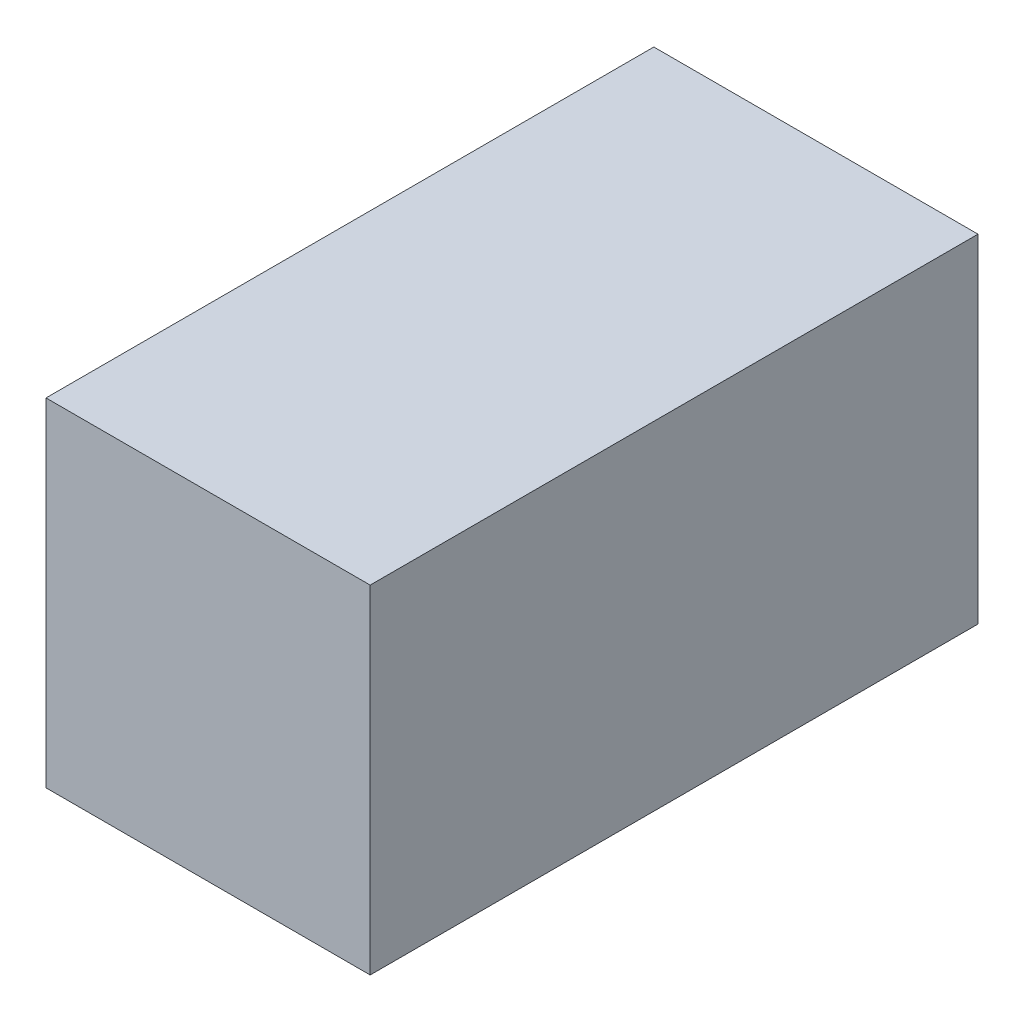
SolidWorks part; units mm, degrees
ref_plane "Front Plane" through (0, 0, 0) normal (0, 0, 1) x (1, 0, 0)
ref_plane "Top Plane" through (0, 0, 0) normal (0, 1, 0) x (1, 0, 0)
ref_plane "Right Plane" through (0, 0, 0) normal (1, 0, 0) x (0, 0, -1)
sketch "Sketch1" plane through (0, 0, 0) normal (1, 0, 0) x (0, 0, -1)
  line L1 (-25.0839, 20.618) -> (32.0661, 20.618)
  line L2 (-25.0839, 20.618) -> (-25.0839, -11.132)
  line L3 (-25.0839, -11.132) -> (32.0661, -11.132)
  line L4 (32.0661, 20.618) -> (32.0661, -11.132)
  dimension "D1" = 57.15
  dimension "D2" = 31.75
extrude "Boss-Extrude1" add sketch "Sketch1" along normal blind 30.48
